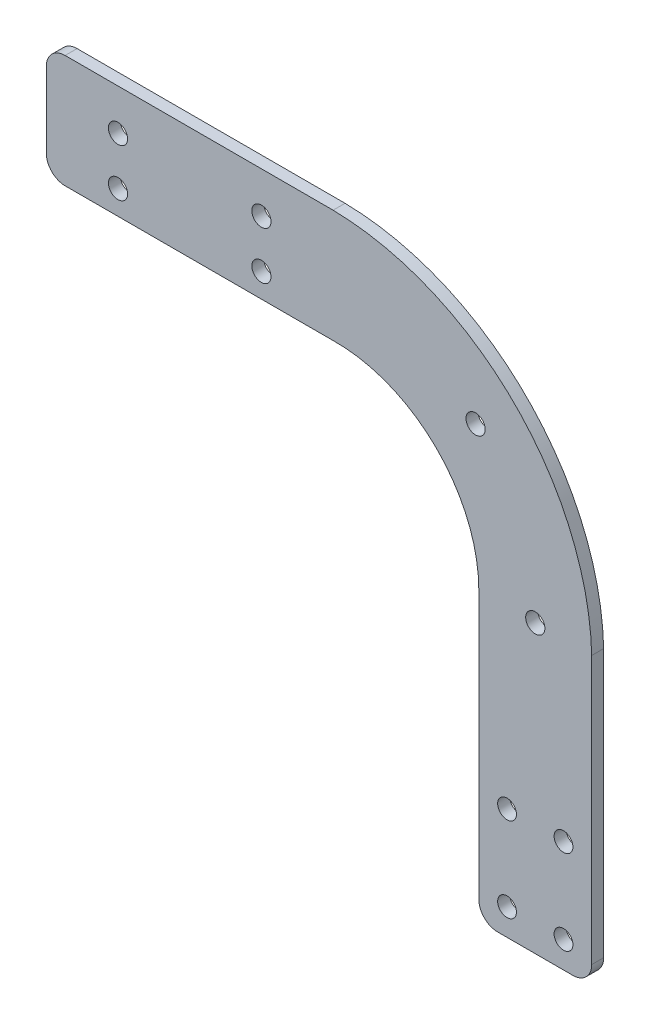
SolidWorks part; units mm, degrees
material "6061-T6 (SS)"
ref_plane "Front Plane" through (0, 0, 0) normal (0, 0, 1) x (1, 0, 0)
ref_plane "Top Plane" through (0, 0, 0) normal (0, 1, 0) x (1, 0, 0)
ref_plane "Right Plane" through (0, 0, 0) normal (1, 0, 0) x (0, 0, -1)
sketch "Sketch1" plane through (0, 0, 0) normal (0, 0, 1) x (1, 0, 0)
  line L1 (-38.1, 15) -> (38.1, 15)
  line L2 (-38.1, 15) -> (-38.1, -15)
  line L3 (-38.1, -15) -> (38.1, -15)
  line L4 (38.1, 15) -> (38.1, -15)
  point P4 (0, 15)
  point P6 (38.1, 0)
  dimension "D1" = 76.2
  dimension "D2" = 30
extrude "Boss-Extrude1" add sketch "Sketch1" along normal blind 3.175
sketch "Sketch3" plane through (0, 0, 0) normal (0, 0, -1) x (-1, 0, 0)
  line L0 (38.1, -15) -> (-38.1, -15) construction
  line L1 (-111.8175, -132.6332) -> (-111.8175, -92.845) construction
  line L4 (-111.8175, -132.6332) -> (-111.8175, -92.845) construction
  line L5 (-106.8175, -129.231) -> (-76.8175, -129.231)
  line L6 (-106.8175, -129.231) -> (-106.8175, -53.1)
  line L8 (-76.8175, -129.231) -> (-76.8175, -53.1)
  line L9 (-71.8175, -102.77) -> (-71.8175, -134.4606) construction
  line L12 (-73.4748, -129.731) -> (-108.6425, -129.731)
  line L14 (38.1, -15) -> (38.1, 15)
  line L15 (38.1, 15) -> (-38.1, 15)
  line L16 (-38.1, 15) -> (-38.1, -15)
  line L17 (-38.1, -15) -> (38.1, -15)
  line L20 (-38.1, 15) -> (-38.1, -15)
  arc A1 (-38.1, 15) -> (-106.8175, -53.1) centre (-36.9013, -54.9299) ccw
  arc A3 (-76.8175, -53.1) -> (-38.1, -15) centre (-38.7126, -53.1) cw
  line M9 (-38.1, 15) -> (-38.1, -15)
  dimension "D1" = 38.7175
  dimension "D2" = 30
  dimension "D6" = 38.1
  dimension "D4" = 0
extrude "Boss-Extrude2" add sketch "Sketch3" against normal up to surface (3.175 mm away) contours A1 L6 L5 L8 A3 M9 up to face at (0, 0, 3.175)
fillet "Fillet1" radius 5 4 edges at (106.8175, -129.231, 1.5875) (76.8175, -129.231, 1.5875) (-38.1, 15, 1.5875) (-38.1, -15, 1.5875)
sketch "Sketch5" plane through (0, 0, 3.175) normal (0, 0, 1) x (1, 0, 0)
  line L0 (84.3175, -99.67) -> (84.3175, -122.17) construction
  line L1 (99.3175, -99.67) -> (99.3175, -122.17) construction
  line L2 (101.8175, -129.231) -> (81.8175, -129.231) construction
  line L3 (106.8175, -124.231) -> (106.8175, -53.1) construction
  line L4 (76.8175, -124.231) -> (76.8175, -53.1) construction
  circle A4 centre (99.3175, -122.17) radius 2.5
  circle A5 centre (84.3175, -122.17) radius 2.5
  circle A6 centre (84.3175, -99.67) radius 2.5
  circle A7 centre (99.3175, -99.67) radius 2.5
  dimension "D1" = 7.061
  dimension "D2" = 7.5
  dimension "D3" = 7.5
extrude "Cut-Extrude2" cut sketch "Sketch5" against normal through all
sketch "Sketch6" plane through (0, 0, 0) normal (0, 0, -1) x (-1, 0, 0)
  circle A4 centre (-19.05, -8.6) radius 2.55
  circle A5 centre (19.05, -8.6) radius 2.55
  circle A6 centre (19.05, 4.1) radius 2.55
  circle A7 centre (-19.05, 4.1) radius 2.55
extrude "Cut-Extrude3" cut sketch "Sketch6" against normal through all
sketch "Sketch7" plane through (0, 0, 0) normal (0, 0, -1) x (-1, 0, 0)
  line L2 (-91.8175, -124.231) -> (-91.8175, -53.1)
  line L3 (-91.8175, -124.231) -> (-91.8175, -53.1) construction
  circle A1 centre (-75.9604, -15.2485) radius 2.55
  arc A2 (-37.8589, -0.0019) -> (-91.8175, -53.1) centre (-38.7126, -53.1) ccw
  arc A3 (-37.8589, -0.0019) -> (-91.8175, -53.1) centre (-38.7126, -53.1) ccw construction
  circle A4 centre (-91.8175, -53.1) radius 2.55
  dimension "D2" = 5.1
  dimension "D3" = 5.1
  dimension "D1" = 15
extrude "Cut-Extrude4" cut sketch "Sketch7" against normal blind 10
